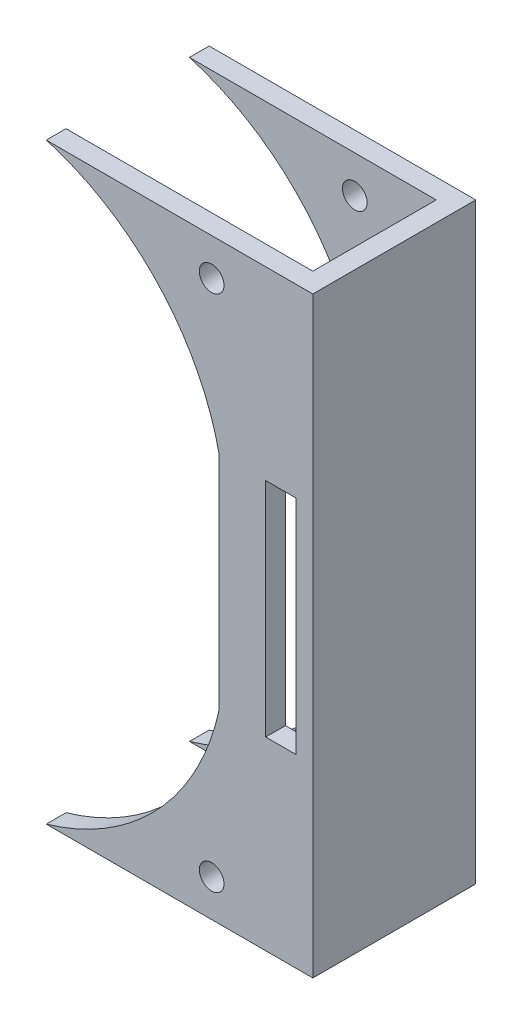
SolidWorks part; units mm, degrees
ref_plane "Front Plane" through (0, 0, 0) normal (0, 0, 1) x (1, 0, 0)
ref_plane "Top Plane" through (0, 0, 0) normal (0, 1, 0) x (1, 0, 0)
ref_plane "Right Plane" through (0, 0, 0) normal (1, 0, 0) x (0, 0, -1)
sketch "Sketch3" plane through (0, 0, 0) normal (0, 0, 1) x (1, 0, 0)
  line L0 (14.3358, 60) -> (14.3358, -60)
  line L1 (14.3358, -60) -> (-22.6642, -60)
  line L2 (12.3358, 22.5) -> (12.3358, -22.5)
  line L3 (14.3358, 60) -> (-22.6642, 60)
  line L4 (14.3358, 0) -> (10.3358, 0) construction
  line L5 (14.3358, 60) -> (27.3358, 60)
  line L6 (27.3358, 60) -> (27.3358, -60)
  line L7 (27.3358, -60) -> (14.3358, -60)
  line L8 (0, 0) -> (24.6715, 0) construction
  arc A2 (12.3358, 22.5) -> (-22.6642, 60) centre (-36.6774, 11.8377) ccw
  arc A3 (-22.6642, -60) -> (12.3358, -22.5) centre (-36.6774, -11.8377) ccw
  point P8 (12.3358, 0)
  point P10 (-0.008, 46.0625)
  point P12 (-0.008, -46.0625)
  dimension "D5" = 2
  dimension "D1" = 120
  dimension "D2" = 37
  dimension "D3" = 37
  dimension "D4" = 45
  dimension "D6" = 20
  dimension "D7" = 20
  dimension "D8" = 13
extrude "Boss-Extrude1" add sketch "Sketch3" along normal blind 4 contours L7 L6 L5 L0 | L4 L0 L3 A2 L2 | L0 L4 L2 A3 L1
ref_plane "Plane3" through (0, 0, -12.5) normal (0, 0, 1) x (1, 0, 0)
mirror "Mirror4" about plane through (0, 0, -12.5) normal (0, 0, 1) of bodies 101
sketch "Sketch11" plane through (27.3358, 0, 0) normal (1, 0, 0) x (0, 0, -1)
  line L1 (-4, 60) -> (29, 60)
  line L2 (-4, 60) -> (-4, -60)
  line L3 (-4, -60) -> (29, -60)
  line L4 (29, 60) -> (29, -60)
extrude "Boss-Extrude4" add sketch "Sketch11" along normal blind 4
sketch "Sketch12" plane through (0, 0, 4) normal (0, 0, 1) x (1, 0, 0)
  line L0 (-22.6642, 60) -> (31.3358, 60) construction
  line L1 (31.3358, 60) -> (31.3358, -60) construction
  circle A0 centre (10.8358, 52.5) radius 2.5
  dimension "D1" = 5
  dimension "D2" = 7.5
  dimension "D3" = 20.5
extrude "Cut-Extrude3" cut sketch "Sketch12" against normal through all
mirror "Mirror5" about plane through (0, 0, 0) normal (0, 1, 0) of "Cut-Extrude3"
sketch "Sketch13" plane through (0, 0, 4) normal (0, 0, 1) x (1, 0, 0)
  line L0 (31.3358, 60) -> (31.3358, -60) construction
  line L1 (21.7844, -22.5) -> (27.8872, -22.5)
  line L2 (21.7844, -22.5) -> (21.7844, 22.5)
  line L3 (21.7844, 22.5) -> (27.8872, 22.5)
  line L4 (27.8872, -22.5) -> (27.8872, 22.5)
  line L5 (21.7844, -22.5) -> (27.8872, 22.5) construction
  line L6 (21.7844, 22.5) -> (27.8872, -22.5) construction
  line L7 (12.3358, 0) -> (29.0962, 0) construction
  line L8 (12.3358, 22.5) -> (12.3358, -22.5) construction
  point P0 (24.8358, 0)
  point P12 (0, 0)
  dimension "D1" = 6.5
  dimension "D2" = 45
extrude "Cut-Extrude4" cut sketch "Sketch13" against normal through all
sketch "Sketch15" plane through (0, 0, -25) normal (0, 0, 1) x (1, 0, 0)
  line L1 (14.3358, -41.5) -> (21.8358, -41.5)
  line L2 (14.3358, -41.5) -> (14.3358, -35.5)
  line L3 (14.3358, -35.5) -> (21.8358, -35.5)
  line L4 (21.8358, -41.5) -> (21.8358, -35.5)
  line L5 (14.3358, -41.5) -> (21.8358, -35.5) construction
  line L6 (14.3358, -35.5) -> (21.8358, -41.5) construction
  circle A0 centre (10.8358, -52.5) radius 2.5 construction
  point P0 (18.0858, -38.5)
  point P9 (-36.2242, -23.6807)
  point P10 (-35.1012, -18.3063)
  dimension "D4" = 3.5
  dimension "D1" = 7.5
  dimension "D2" = 6
  dimension "D3" = 14
extrude "Cut-Extrude5" cut sketch "Sketch15" against normal through all
